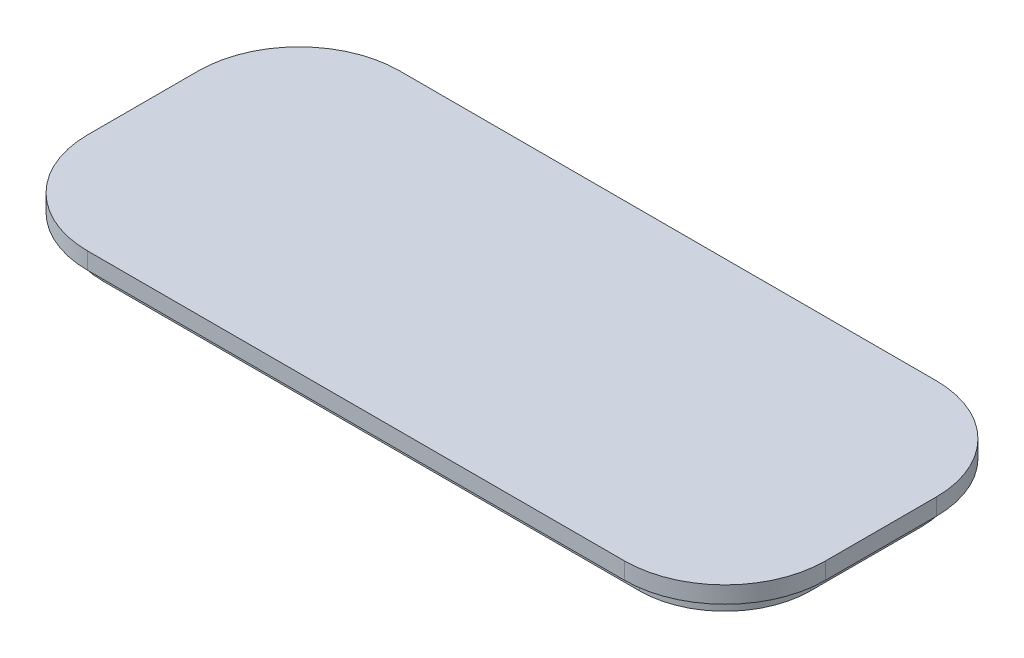
SolidWorks part; units mm, degrees
ref_plane "前基準面" through (0, 0, 0) normal (0, 0, 1) x (1, 0, 0)
ref_plane "上基準面" through (0, 0, 0) normal (0, 1, 0) x (1, 0, 0)
ref_plane "右基準面" through (0, 0, 0) normal (1, 0, 0) x (0, 0, -1)
sketch "草圖1" plane through (0, 0, 0) normal (0, 1, 0) x (1, 0, 0)
  line L1 (-110, 46.5) -> (110, 46.5)
  line L2 (-110, 46.5) -> (-110, -46.5)
  line L3 (-110, -46.5) -> (110, -46.5)
  line L4 (110, 46.5) -> (110, -46.5)
  line L5 (-110, 46.5) -> (110, -46.5) construction
  line L6 (-110, -46.5) -> (110, 46.5) construction
  point P0 (0, 0)
  dimension "D1" = 220
  dimension "D2" = 93
extrude "填料-伸長1" add sketch "草圖1" along normal blind 5
fillet "圓角1" radius 30 4 edges at (110, 2.5, -46.5) (110, 2.5, 46.5) (-110, 2.5, 46.5) (-110, 2.5, -46.5)
sketch "草圖2" plane through (0, 0, 0) normal (0, -1, 0) x (1, 0, 0)
  line L8 (-80, -42) -> (80, -42)
  line L9 (105.5, -16.5) -> (105.5, 16.5)
  line L10 (80, 42) -> (-80, 42)
  line L11 (-105.5, 16.5) -> (-105.5, -16.5)
  line L12 (-80, -42) -> (80, -42)
  line L13 (105.5, -16.5) -> (105.5, 16.5)
  line L14 (80, 42) -> (-80, 42)
  line L15 (-105.5, 16.5) -> (-105.5, -16.5)
  line L20 (-80, -36.5) -> (80, -36.5)
  line L21 (100, -16.5) -> (100, 16.5)
  line L22 (80, 36.5) -> (-80, 36.5)
  line L23 (-100, 16.5) -> (-100, -16.5)
  line L24 (-80, -36.5) -> (80, -36.5)
  line L25 (100, -16.5) -> (100, 16.5)
  line L26 (80, 36.5) -> (-80, 36.5)
  line L27 (-100, 16.5) -> (-100, -16.5)
  arc A8 (80, -42) -> (105.5, -16.5) centre (80, -16.5) ccw
  arc A9 (105.5, 16.5) -> (80, 42) centre (80, 16.5) ccw
  arc A10 (-80, 42) -> (-105.5, 16.5) centre (-80, 16.5) ccw
  arc A11 (-105.5, -16.5) -> (-80, -42) centre (-80, -16.5) ccw
  arc A12 (80, -42) -> (105.5, -16.5) centre (80, -16.5) ccw
  arc A13 (105.5, 16.5) -> (80, 42) centre (80, 16.5) ccw
  arc A14 (-80, 42) -> (-105.5, 16.5) centre (-80, 16.5) ccw
  arc A15 (-105.5, -16.5) -> (-80, -42) centre (-80, -16.5) ccw
  arc A20 (80, -36.5) -> (100, -16.5) centre (80, -16.5) ccw
  arc A21 (100, 16.5) -> (80, 36.5) centre (80, 16.5) ccw
  arc A22 (-80, 36.5) -> (-100, 16.5) centre (-80, 16.5) ccw
  arc A23 (-100, -16.5) -> (-80, -36.5) centre (-80, -16.5) ccw
  arc A24 (80, -36.5) -> (100, -16.5) centre (80, -16.5) ccw
  arc A25 (100, 16.5) -> (80, 36.5) centre (80, 16.5) ccw
  arc A26 (-80, 36.5) -> (-100, 16.5) centre (-80, 16.5) ccw
  arc A27 (-100, -16.5) -> (-80, -36.5) centre (-80, -16.5) ccw
  dimension "D1" = 4.5
  dimension "D2" = 10
extrude "填料-伸長2" add sketch "草圖2" along normal blind 5
